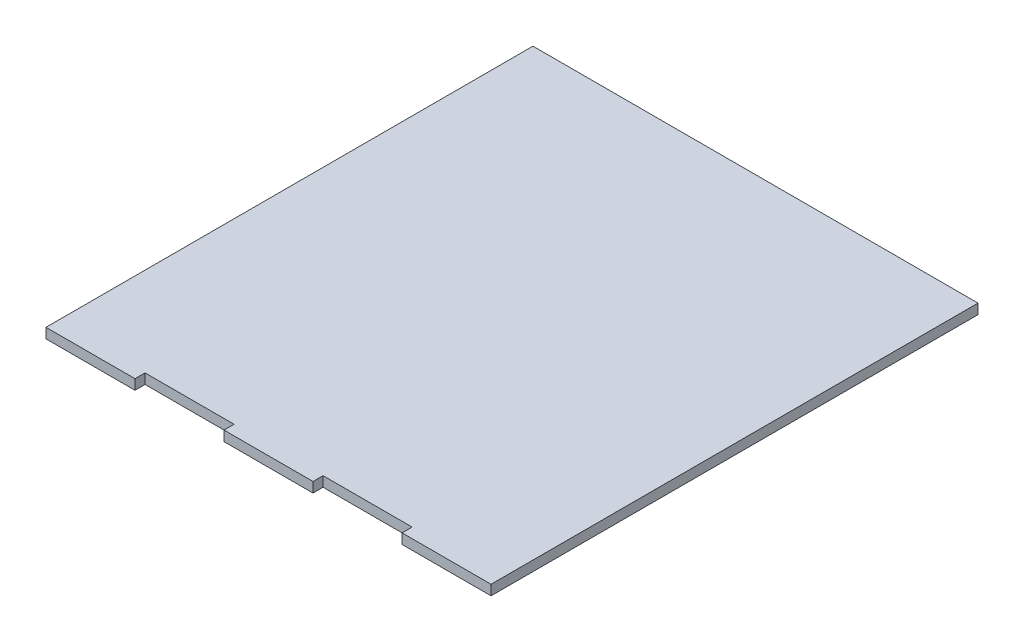
SolidWorks part; units mm, degrees
ref_plane "Front Plane" through (0, 0, 0) normal (0, 0, 1) x (1, 0, 0)
ref_plane "Top Plane" through (0, 0, 0) normal (0, 1, 0) x (1, 0, 0)
ref_plane "Right Plane" through (0, 0, 0) normal (1, 0, 0) x (0, 0, -1)
sketch "Sketch1" plane through (0, 0, 0) normal (0, 1, 0) x (1, 0, 0)
  line L1 (-69.721, 407.3307) -> (299.4045, 407.3307)
  line L2 (-69.721, 407.3307) -> (-69.721, 3.4402)
  line L3 (-69.721, 3.4402) -> (299.4045, 3.4402)
  line L4 (299.4045, 407.3307) -> (299.4045, 3.4402)
  dimension "D1" = 369.1255
  dimension "D2" = 403.8905
extrude "Boss-Extrude1" add sketch "Sketch1" along normal blind 8.3312
sketch "Sketch2" plane through (0, 0, 0) normal (0, -1, 0) x (1, 0, 0)
  line L0 (114.8418, -3.4402) -> (114.8418, -407.3307) construction
  line L1 (-69.721, -3.4402) -> (299.4045, -3.4402) construction
  line L2 (299.4045, -407.3307) -> (-69.721, -407.3307) construction
  line L3 (225.5794, -11.7714) -> (151.7543, -11.7714)
  line L4 (-69.721, -407.3307) -> (-69.721, -3.4402) construction
  line L6 (151.7543, -3.4402) -> (151.7543, -11.7714)
  line L7 (4.1041, -3.4402) -> (77.9292, -3.4402)
  line L8 (4.1041, -3.4402) -> (4.1041, -11.7714)
  line L9 (4.1041, -11.7714) -> (77.9292, -11.7714)
  line L10 (77.9292, -3.4402) -> (77.9292, -11.7714)
  line L11 (225.5794, -3.4402) -> (151.7543, -3.4402)
  line L12 (225.5794, -3.4402) -> (225.5794, -11.7714)
  dimension "D1" = 8.3312
  dimension "D2" = 73.8251
  dimension "D3" = 73.8251
extrude "Cut-Extrude1" cut sketch "Sketch2" against normal through all
equation "\"D1@Sketch1\"=\"Base Length@Assembled Container.Assembly\""
equation "\"D2@Sketch1\"=\"Side Height@Assembled Container.Assembly\""
equation "\"D1@Boss-Extrude1\"=\"Acrylic Thickness@Assembled Container.Assembly\""
equation "\"D1@Sketch2\"=\"Acrylic Thickness@Assembled Container.Assembly\""
equation "\"D2@Sketch2\"=\"Lid Long Side Outer Cutout@Assembled Container.Assembly\""
equation "\"D3@Sketch2\"=\"Lid Long Side Overhang@Assembled Container.Assembly\""
